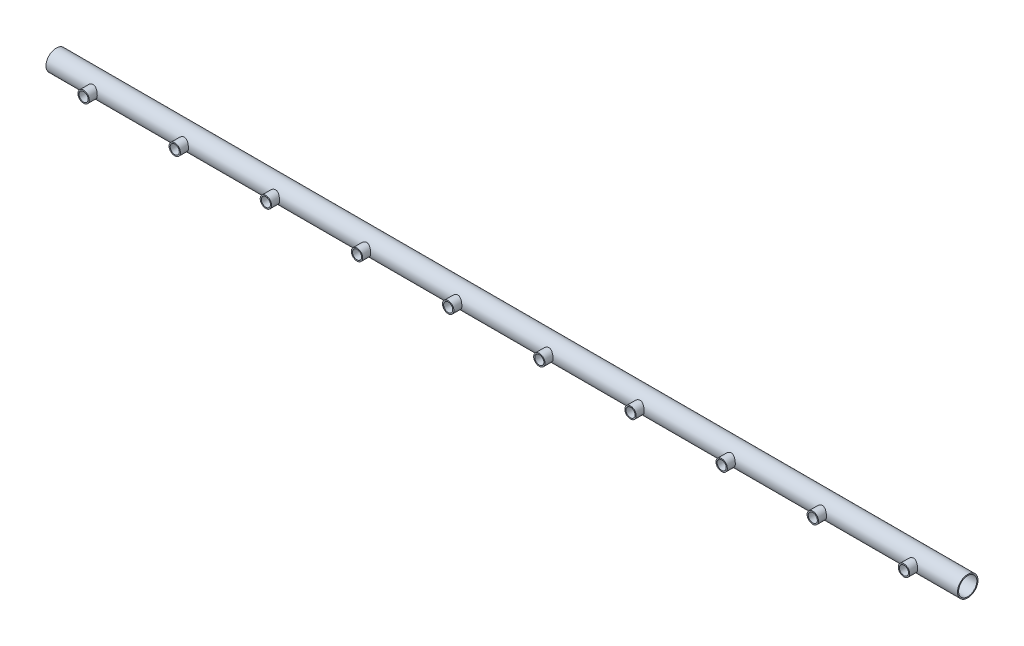
SolidWorks part; units mm, degrees
ref_plane "Front Plane" through (0, 0, 0) normal (0, 0, 1) x (1, 0, 0)
ref_plane "Top Plane" through (0, 0, 0) normal (0, 1, 0) x (1, 0, 0)
ref_plane "Right Plane" through (0, 0, 0) normal (1, 0, 0) x (0, 0, -1)
sketch "Sketch1" plane through (0, 0, 0) normal (1, 0, 0) x (0, 0, -1)
  circle A0 centre (0, 0) radius 20
  circle A1 centre (0, 0) radius 22.5
  dimension "D1" = 40
  dimension "D2" = 45
extrude "Boss-Extrude1" add sketch "Sketch1" along normal mid plane 2000
sketch "Sketch2" plane through (0, 0, 0) normal (0, 0, 1) x (1, 0, 0)
  line L0 (0, 0) -> (0, 20.6476)
  line L1 (24.75, 0) -> (-24.75, 0) construction
  line L2 (0, -24.75) -> (0, 24.75) construction
  circle A0 centre (100, 0) radius 12.5
  circle A1 centre (100, 0) radius 10
  circle A2 centre (300, 0) radius 10
  circle A3 centre (300, 0) radius 12.5
  circle A4 centre (500, 0) radius 12.5
  circle A5 centre (500, 0) radius 10
  circle A6 centre (700, 0) radius 10
  circle A7 centre (700, 0) radius 12.5
  circle A8 centre (900, 0) radius 10
  circle A9 centre (900, 0) radius 12.5
  circle A10 centre (-900, 0) radius 10
  circle A11 centre (-900, 0) radius 12.5
  circle A12 centre (-700, 0) radius 10
  circle A13 centre (-700, 0) radius 12.5
  circle A14 centre (-500, 0) radius 12.5
  circle A15 centre (-500, 0) radius 10
  circle A16 centre (-300, 0) radius 10
  circle A17 centre (-300, 0) radius 12.5
  circle A18 centre (-100, 0) radius 12.5
  circle A19 centre (-100, 0) radius 10
  dimension "D2" = 25
  dimension "D3" = 20
  dimension "D8" = 20
  dimension "D9" = 25
  dimension "D10" = 25
  dimension "D11" = 20
  dimension "D12" = 25
  dimension "D13" = 20
  dimension "D4" = 100
  dimension "D5" = 200
  dimension "D6" = 200
  dimension "D7" = 200
  dimension "D14" = 200
extrude "Boss-Extrude2" add sketch "Sketch2" along normal blind 40 contours A6 | A10 | A11 | A12 | A13 | A14 | A15 | A17 | A16 | A18 | A19 | A0 | A1 | A3 | A2 | A4 | A5 | A7 | A9 | A8
sketch "Sketch3" plane through (-1000, 0, 0) normal (-1, 0, 0) x (0, 0, 1)
  circle A0 centre (0, 0) radius 20
extrude "Cut-Extrude1" cut sketch "Sketch3" against normal through all
